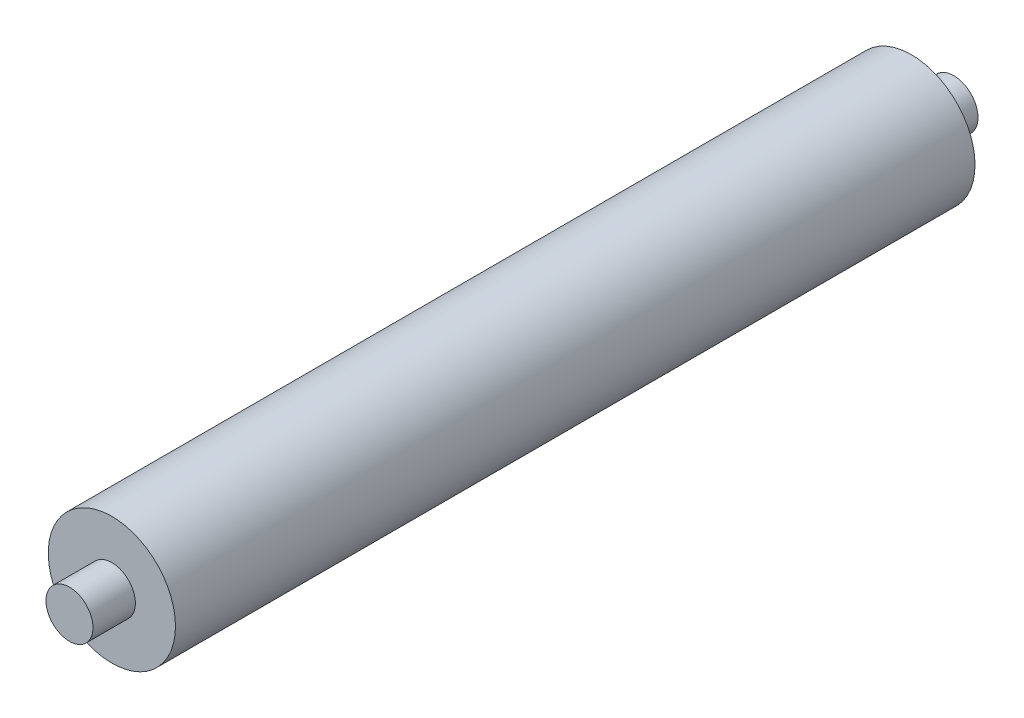
SolidWorks part; units mm, degrees
ref_plane "前视基准面" through (0, 0, 0) normal (0, 0, 1) x (1, 0, 0)
ref_plane "上视基准面" through (0, 0, 0) normal (0, 1, 0) x (1, 0, 0)
ref_plane "右视基准面" through (0, 0, 0) normal (1, 0, 0) x (0, 0, -1)
sketch "草图1" plane through (0, 0, 0) normal (0, 0, 1) x (1, 0, 0)
  circle A0 centre (0, 0) radius 10.5
  dimension "D1" = 21
extrude "凸台-拉伸1" add sketch "草图1" along normal blind 132
sketch "草图2" plane through (0, 0, 132) normal (0, 0, 1) x (1, 0, 0)
  circle A0 centre (0, 0) radius 3.8821
extrude "凸台-拉伸2" add sketch "草图2" along normal blind 7
sketch "草图3" plane through (0, 0, 132) normal (0, 0, 1) x (1, 0, 0)
  circle A0 centre (0, 0) radius 4.5
  dimension "D1" = 9
sketch "草图4" plane through (0, 0, 0) normal (0, 0, -1) x (-1, 0, 0)
  circle A0 centre (0, 0) radius 4.5
  dimension "D1" = 9
sketch "草图5" plane through (0, 0, 0) normal (0, 0, -1) x (-1, 0, 0)
  circle A0 centre (0, 0) radius 4
  dimension "D1" = 8
extrude "凸台-拉伸3" add sketch "草图5" along normal blind 7
